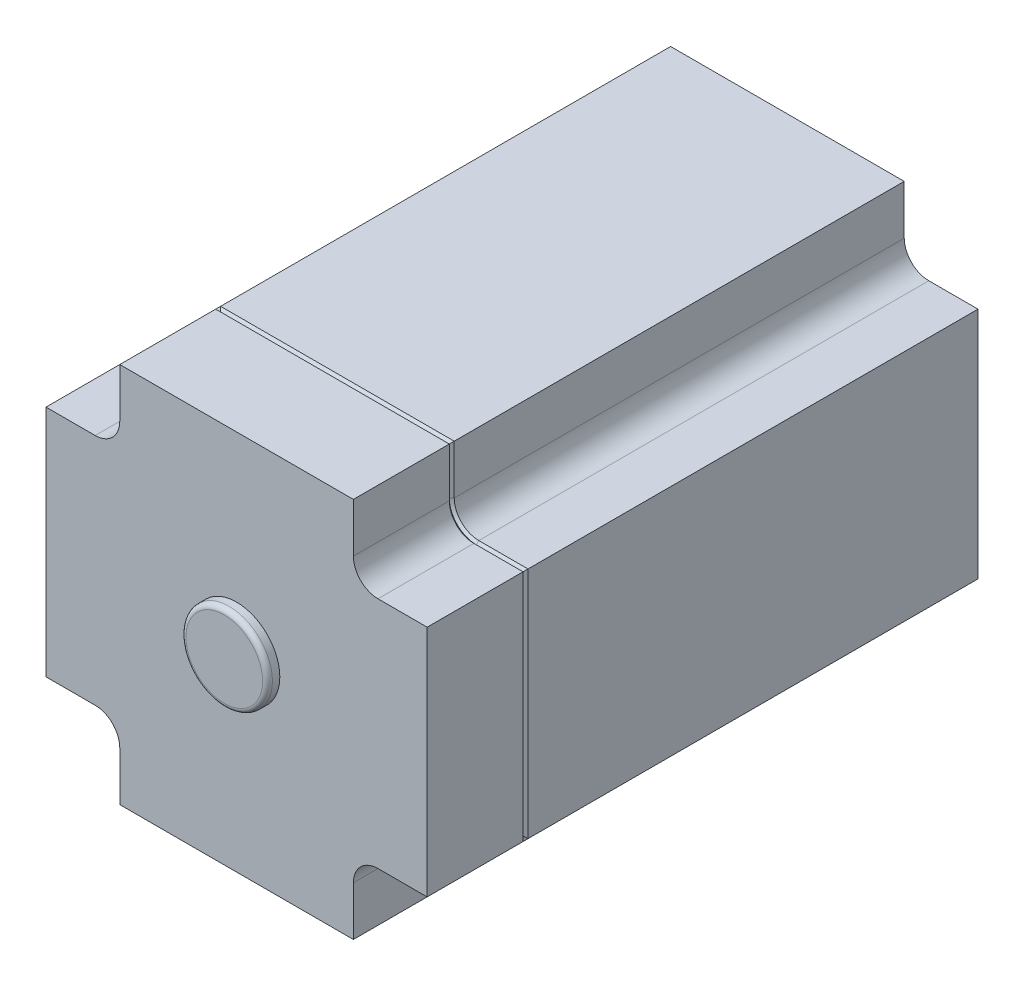
SolidWorks part; units mm, degrees
ref_plane "Ön Düzlem" through (0, 0, 0) normal (0, 0, 1) x (1, 0, 0)
ref_plane "Üst Düzlem" through (0, 0, 0) normal (0, 1, 0) x (1, 0, 0)
ref_plane "Sağ Düzlem" through (0, 0, 0) normal (1, 0, 0) x (0, 0, -1)
sketch "Çizim1" plane through (0, 0, 0) normal (0, 0, 1) x (1, 0, 0)
  line L0 (-84.5985, 33.3946) -> (-58.6268, 58.9683)
  line L1 (-84.5985, -41.0317) -> (15.4015, -41.0317)
  line L2 (-84.5985, -41.0317) -> (-84.5985, 58.9683)
  line L3 (-84.5985, 58.9683) -> (15.4015, 58.9683)
  line L4 (15.4015, -41.0317) -> (15.4015, 58.9683)
  line L5 (-84.5985, -41.0317) -> (15.4015, 58.9683) construction
  line L6 (-84.5985, 58.9683) -> (15.4015, -41.0317) construction
  line L7 (-58.6268, -41.0317) -> (-84.5985, -15.06)
  line L8 (-10.1722, -41.0317) -> (15.4015, -15.06)
  line L9 (15.4015, 32.6426) -> (-10.9242, 58.9683)
  point P0 (-34.5985, 8.9683)
  point P11 (-63.3453, 6.1932)
  point P14 (-66.1203, 34.94)
  point P17 (-37.3736, 37.7151)
  point P20 (-50.3594, 21.9542)
  dimension "D1" = 100
  dimension "D2" = 100
  dimension "D4" = 4
extrude "Yükseklik-Ekstrüzyon1" add sketch "Çizim1" along normal blind 13
sketch "Çizim2" plane through (0, 0, 0) normal (0, 0, 1) x (1, 0, 0)
  line L0 (47.5, 77.5) -> (47.5, 57.5)
  line L1 (57.5, 47.5) -> (77.5, 47.5)
  line L2 (47.5, -57.5) -> (47.5, -77.5)
  line L3 (77.5, -47.5) -> (57.5, -47.5)
  line L4 (-57.5, -47.5) -> (-77.5, -47.5)
  line L5 (-47.5, -77.5) -> (-47.5, -57.5)
  line L6 (-47.5, 57.5) -> (-47.5, 77.5)
  line L7 (-77.5, 47.5) -> (-57.5, 47.5)
  line L16 (-77.5, -54.0219) -> (-54.0219, -77.5)
  line L17 (-54.0219, -77.5) -> (54.0219, -77.5)
  line L18 (54.0219, -77.5) -> (77.5, -54.0219)
  line L19 (77.5, -54.0219) -> (77.5, 54.0219)
  line L20 (77.5, 54.0219) -> (54.0219, 77.5)
  line L21 (54.0219, 77.5) -> (-54.0219, 77.5)
  line L22 (-54.0219, 77.5) -> (-77.5, 54.0219)
  line L23 (-77.5, 54.0219) -> (-77.5, -54.0219)
  arc A0 (47.5, 57.5) -> (57.5, 47.5) centre (57.5, 57.5) ccw
  arc A1 (57.5, -47.5) -> (47.5, -57.5) centre (57.5, -57.5) ccw
  arc A2 (-47.5, -57.5) -> (-57.5, -47.5) centre (-57.5, -57.5) ccw
  arc A3 (-57.5, 47.5) -> (-47.5, 57.5) centre (-57.5, 57.5) ccw
  point P31 (0, 0)
  dimension "D4" = 10
  dimension "D2" = 30
  dimension "D3" = 30
  dimension "D5" = 4
extrude "Yükseklik-Ekstrüzyon2" add sketch "Çizim2" along normal blind 224 contours A3 L7 L23 L4 A2 L5 L17 L2 A1 L3 L19 L1 A0 L0 L21 L6
sketch "Çizim5" plane through (0, 0, 224) normal (0, 0, 1) x (1, 0, 0)
  line L12 (56.5, 57.5) -> (56.5, 86.5)
  line L13 (56.5, 86.5) -> (-56.5, 86.5)
  line L14 (-56.5, 86.5) -> (-56.5, 57.5)
  line L15 (-57.5, 56.5) -> (-86.5, 56.5)
  line L16 (-86.5, 56.5) -> (-86.5, -56.5)
  line L17 (-86.5, -56.5) -> (-57.5, -56.5)
  line L18 (-56.5, -57.5) -> (-56.5, -86.5)
  line L19 (-56.5, -86.5) -> (56.5, -86.5)
  line L20 (56.5, -86.5) -> (56.5, -57.5)
  line L21 (57.5, -56.5) -> (86.5, -56.5)
  line L22 (86.5, -56.5) -> (86.5, 56.5)
  line L23 (86.5, 56.5) -> (57.5, 56.5)
  line L24 (46.5, 57.5) -> (46.5, 76.5)
  line L25 (-76.5, 46.5) -> (-76.5, -46.5)
  line L26 (-46.5, 76.5) -> (-46.5, 57.5)
  line L27 (-57.5, 46.5) -> (-76.5, 46.5)
  line L28 (-76.5, 46.5) -> (-76.5, -46.5)
  line L29 (-76.5, -46.5) -> (-57.5, -46.5)
  line L30 (-46.5, -57.5) -> (-46.5, -76.5)
  line L31 (-46.5, -76.5) -> (46.5, -76.5)
  line L32 (46.5, -76.5) -> (46.5, -57.5)
  line L33 (57.5, -46.5) -> (76.5, -46.5)
  line L34 (-46.5, -76.5) -> (46.5, -76.5)
  line L35 (76.5, 46.5) -> (57.5, 46.5)
  line L36 (46.5, 57.5) -> (46.5, 76.5)
  line L38 (-46.5, 76.5) -> (-46.5, 57.5)
  line L39 (-57.5, 46.5) -> (-76.5, 46.5)
  line L41 (-76.5, -46.5) -> (-57.5, -46.5)
  line L42 (-46.5, -57.5) -> (-46.5, -76.5)
  line L44 (46.5, -76.5) -> (46.5, -57.5)
  line L45 (57.5, -46.5) -> (76.5, -46.5)
  line L47 (76.5, 46.5) -> (57.5, 46.5)
  line L48 (46.5, 76.5) -> (-46.5, 76.5) construction
  line L49 (-76.5, 46.5) -> (-76.5, -46.5) construction
  line L50 (-46.5, -76.5) -> (46.5, -76.5) construction
  line L51 (76.5, -46.5) -> (76.5, 46.5) construction
  line L52 (76.5, -46.5) -> (76.5, 46.5)
  line L53 (76.5, -46.5) -> (76.5, 46.5)
  line L54 (46.5, 76.5) -> (-46.5, 76.5)
  line L55 (46.5, 76.5) -> (-46.5, 76.5)
  arc A4 (-57.5, 56.5) -> (-56.5, 57.5) centre (-57.5, 57.5) ccw
  arc A5 (-56.5, -57.5) -> (-57.5, -56.5) centre (-57.5, -57.5) ccw
  arc A6 (57.5, -56.5) -> (56.5, -57.5) centre (57.5, -57.5) ccw
  arc A7 (56.5, 57.5) -> (57.5, 56.5) centre (57.5, 57.5) ccw
  arc A8 (-57.5, 46.5) -> (-46.5, 57.5) centre (-57.5, 57.5) ccw
  arc A9 (-46.5, -57.5) -> (-57.5, -46.5) centre (-57.5, -57.5) ccw
  arc A10 (57.5, -46.5) -> (46.5, -57.5) centre (57.5, -57.5) ccw
  arc A11 (46.5, 57.5) -> (57.5, 46.5) centre (57.5, 57.5) ccw
  arc A12 (-57.5, 46.5) -> (-46.5, 57.5) centre (-57.5, 57.5) ccw
  arc A13 (-46.5, -57.5) -> (-57.5, -46.5) centre (-57.5, -57.5) ccw
  arc A14 (57.5, -46.5) -> (46.5, -57.5) centre (57.5, -57.5) ccw
  arc A15 (46.5, 57.5) -> (57.5, 46.5) centre (57.5, 57.5) ccw
  dimension "D1" = 1
  dimension "D2" = 10
ref_plane "Düzlem1" through (0, 0, 184) normal (0, 0, 1) x (1, 0, 0)
sketch "Çizim7" plane through (0, 0, 184) normal (0, 0, 1) x (1, 0, 0)
  line L12 (57.5, -56.5) -> (86.5, -56.5)
  line L13 (86.5, -56.5) -> (86.5, 56.5)
  line L14 (86.5, 56.5) -> (57.5, 56.5)
  line L15 (56.5, 57.5) -> (56.5, 86.5)
  line L16 (56.5, 86.5) -> (-56.5, 86.5)
  line L17 (-56.5, 86.5) -> (-56.5, 57.5)
  line L18 (-57.5, 56.5) -> (-86.5, 56.5)
  line L19 (-86.5, 56.5) -> (-86.5, -56.5)
  line L20 (-86.5, -56.5) -> (-57.5, -56.5)
  line L21 (-56.5, -57.5) -> (-56.5, -86.5)
  line L22 (-56.5, -86.5) -> (56.5, -86.5)
  line L23 (56.5, -86.5) -> (56.5, -57.5)
  line L24 (57.5, -56.5) -> (86.5, -56.5)
  line L25 (86.5, -56.5) -> (86.5, 56.5)
  line L26 (86.5, 56.5) -> (57.5, 56.5)
  line L27 (56.5, 57.5) -> (56.5, 86.5)
  line L28 (56.5, 86.5) -> (-56.5, 86.5)
  line L29 (-56.5, 86.5) -> (-56.5, 57.5)
  line L30 (-57.5, 56.5) -> (-86.5, 56.5)
  line L31 (-86.5, 56.5) -> (-86.5, -56.5)
  line L32 (-86.5, -56.5) -> (-57.5, -56.5)
  line L33 (-56.5, -57.5) -> (-56.5, -86.5)
  line L34 (-56.5, -86.5) -> (56.5, -86.5)
  line L35 (56.5, -86.5) -> (56.5, -57.5)
  line L36 (46.5, -76.5) -> (46.5, -57.5)
  line L37 (57.5, -46.5) -> (76.5, -46.5)
  line L38 (-46.5, -76.5) -> (46.5, -76.5)
  line L39 (76.5, 46.5) -> (57.5, 46.5)
  line L40 (46.5, 57.5) -> (46.5, 76.5)
  line L41 (-46.5, -76.5) -> (46.5, -76.5)
  line L42 (-46.5, 76.5) -> (-46.5, 57.5)
  line L43 (-57.5, 46.5) -> (-76.5, 46.5)
  line L44 (-76.5, 46.5) -> (-76.5, -46.5)
  line L45 (-76.5, -46.5) -> (-57.5, -46.5)
  line L46 (-46.5, -57.5) -> (-46.5, -76.5)
  line L47 (-76.5, 46.5) -> (-76.5, -46.5)
  line L48 (46.5, -76.5) -> (46.5, -57.5)
  line L49 (57.5, -46.5) -> (76.5, -46.5)
  line L51 (76.5, 46.5) -> (57.5, 46.5)
  line L52 (46.5, 57.5) -> (46.5, 76.5)
  line L54 (-46.5, 76.5) -> (-46.5, 57.5)
  line L55 (-57.5, 46.5) -> (-76.5, 46.5)
  line L57 (-76.5, -46.5) -> (-57.5, -46.5)
  line L58 (-46.5, -57.5) -> (-46.5, -76.5)
  line L60 (46.5, 76.5) -> (-46.5, 76.5)
  line L61 (46.5, 76.5) -> (-46.5, 76.5)
  line L62 (76.5, -46.5) -> (76.5, 46.5)
  line L63 (76.5, -46.5) -> (76.5, 46.5)
  arc A4 (56.5, 57.5) -> (57.5, 56.5) centre (57.5, 57.5) ccw
  arc A5 (-57.5, 56.5) -> (-56.5, 57.5) centre (-57.5, 57.5) ccw
  arc A6 (-56.5, -57.5) -> (-57.5, -56.5) centre (-57.5, -57.5) ccw
  arc A7 (57.5, -56.5) -> (56.5, -57.5) centre (57.5, -57.5) ccw
  arc A8 (56.5, 57.5) -> (57.5, 56.5) centre (57.5, 57.5) ccw
  arc A9 (-57.5, 56.5) -> (-56.5, 57.5) centre (-57.5, 57.5) ccw
  arc A10 (-56.5, -57.5) -> (-57.5, -56.5) centre (-57.5, -57.5) ccw
  arc A11 (57.5, -56.5) -> (56.5, -57.5) centre (57.5, -57.5) ccw
  arc A12 (57.5, -46.5) -> (46.5, -57.5) centre (57.5, -57.5) ccw
  arc A13 (46.5, 57.5) -> (57.5, 46.5) centre (57.5, 57.5) ccw
  arc A14 (-57.5, 46.5) -> (-46.5, 57.5) centre (-57.5, 57.5) ccw
  arc A15 (-46.5, -57.5) -> (-57.5, -46.5) centre (-57.5, -57.5) ccw
  arc A16 (57.5, -46.5) -> (46.5, -57.5) centre (57.5, -57.5) ccw
  arc A17 (46.5, 57.5) -> (57.5, 46.5) centre (57.5, 57.5) ccw
  arc A18 (-57.5, 46.5) -> (-46.5, 57.5) centre (-57.5, 57.5) ccw
  arc A19 (-46.5, -57.5) -> (-57.5, -46.5) centre (-57.5, -57.5) ccw
  dimension "D1" = 0
  dimension "D2" = 0
extrude "Kes-Ekstrüzyon1" cut sketch "Çizim7" against normal blind 1 draft 45 and the other way blind 1 draft 45
sketch "Çizim8" plane through (0, 0, 224) normal (0, 0, 1) x (1, 0, 0)
  circle A0 centre (0, 0) radius 17.5818
extrude "Yükseklik-Ekstrüzyon3" add sketch "Çizim8" along normal blind 5
fillet "Radyus2" radius 2 1 edges at (17.5818, 0, 229)
